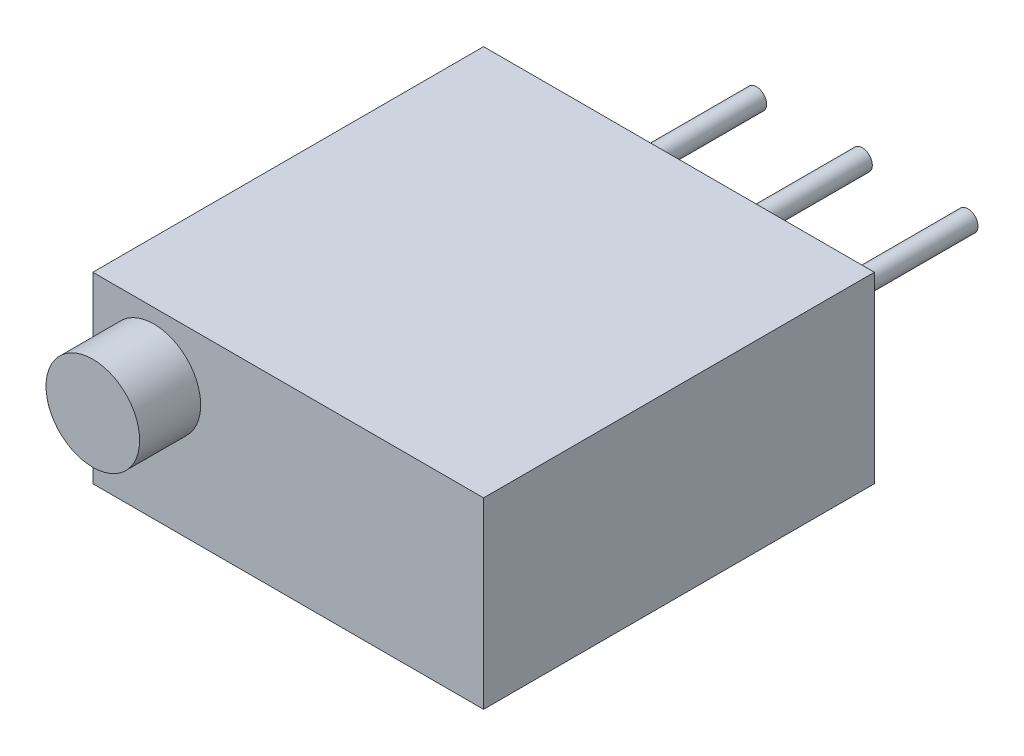
SolidWorks part; units mm, degrees
ref_plane "前视" through (0, 0, 0) normal (0, 0, 1) x (1, 0, 0)
ref_plane "上视" through (0, 0, 0) normal (0, 1, 0) x (1, 0, 0)
ref_plane "右视" through (0, 0, 0) normal (1, 0, 0) x (0, 0, -1)
sketch "草图1" plane through (0, 0, 0) normal (0, 1, 0) x (1, 0, 0)
  line L0 (0, 81.3418) -> (0, -101.3275) construction
  line L1 (-87.3375, 0) -> (113.7186, 0) construction
  line L3 (-4.8, 4.8) -> (4.8, 4.8)
  line L4 (-4.8, 4.8) -> (-4.8, -4.8)
  line L5 (-4.8, -4.8) -> (4.8, -4.8)
  line L6 (4.8, 4.8) -> (4.8, -4.8)
  dimension "D1" = 9.6
  dimension "D2" = 9.6
extrude "拉伸1" add sketch "草图1" along normal blind 4.5
sketch "草图3" plane through (0, 0, -4.8) normal (0, 0, -1) x (-1, 0, 0)
  line L0 (-5.1663, 2.25) -> (6.6013, 2.25) construction
  line L2 (0, 5.9307) -> (0, -2.165) construction
  circle A0 centre (0, 2.25) radius 0.25
  circle A1 centre (2.596, 2.25) radius 0.25
  circle A2 centre (-2.596, 2.25) radius 0.25
  dimension "D1" = 0.5
extrude "拉伸3" add sketch "草图3" along normal blind 4.5
sketch "草图4" plane through (0, 0, 4.8) normal (0, 0, 1) x (1, 0, 0)
  line L0 (-4.8, 4.5) -> (-4.8, 0) construction
  line L1 (-4.8, 4.5) -> (4.8, 4.5) construction
  circle A0 centre (-3.3, 3) radius 1.15
  dimension "D1" = 2.3
  dimension "D2" = 1.5
  dimension "D3" = 1.5
extrude "拉伸4" add sketch "草图4" along normal blind 1.5
